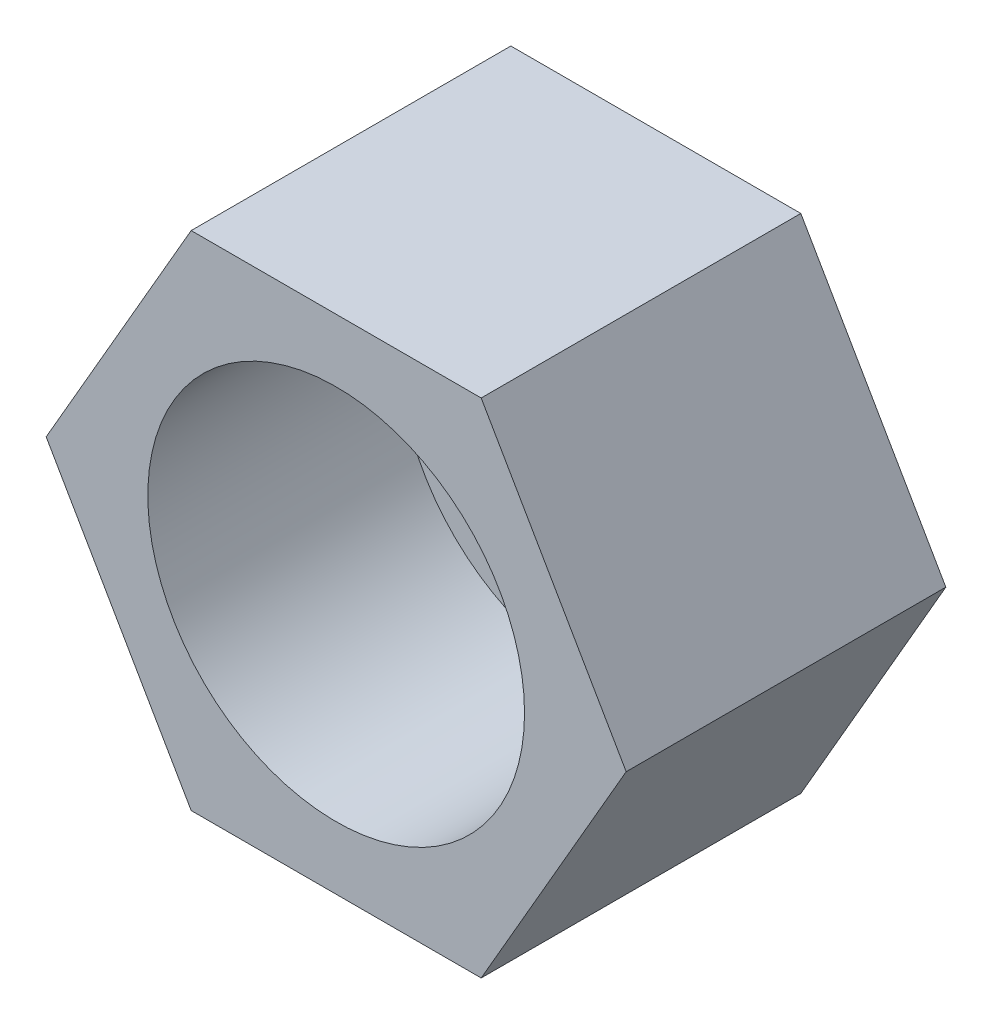
SolidWorks part; units mm, degrees
material "Stahl verzinkt"
ref_plane "Vorne" through (0, 0, 0) normal (0, 0, 1) x (1, 0, 0)
ref_plane "Oben" through (0, 0, 0) normal (0, 1, 0) x (1, 0, 0)
ref_plane "Rechts" through (0, 0, 0) normal (1, 0, 0) x (0, 0, -1)
sketch "Skizze1" plane through (0, 0, 0) normal (0, 0, 1) x (1, 0, 0)
  line L1 (-12.7017, 0) -> (-6.3509, -11)
  line L2 (-6.3509, -11) -> (6.3509, -11)
  line L3 (6.3509, -11) -> (12.7017, 0)
  line L4 (12.7017, 0) -> (6.3509, 11)
  line L5 (6.3509, 11) -> (-6.3509, 11)
  line L6 (-6.3509, 11) -> (-12.7017, 0)
  circle A0 centre (0, 0) radius 11 construction
  dimension "D1" = 22
extrude "Linear austragen1" add sketch "Skizze1" along normal blind 14
sketch "Skizze2" plane through (0, 0, 14) normal (0, 0, 1) x (1, 0, 0)
  circle A0 centre (0, 0) radius 6.9
  dimension "D1" = 13.8
extrude "Schnitt-Linear austragen1" cut sketch "Skizze2" against normal through all
sketch "Skizze3" plane through (0, 0, 14) normal (0, 0, 1) x (1, 0, 0)
  circle A0 centre (0, 0) radius 8.25
  dimension "D1" = 16.5
extrude "Schnitt-Linear austragen2" cut sketch "Skizze3" against normal blind 11
cosmetic thread "Gewindedarstellung1" parameters "D2"=16.6
